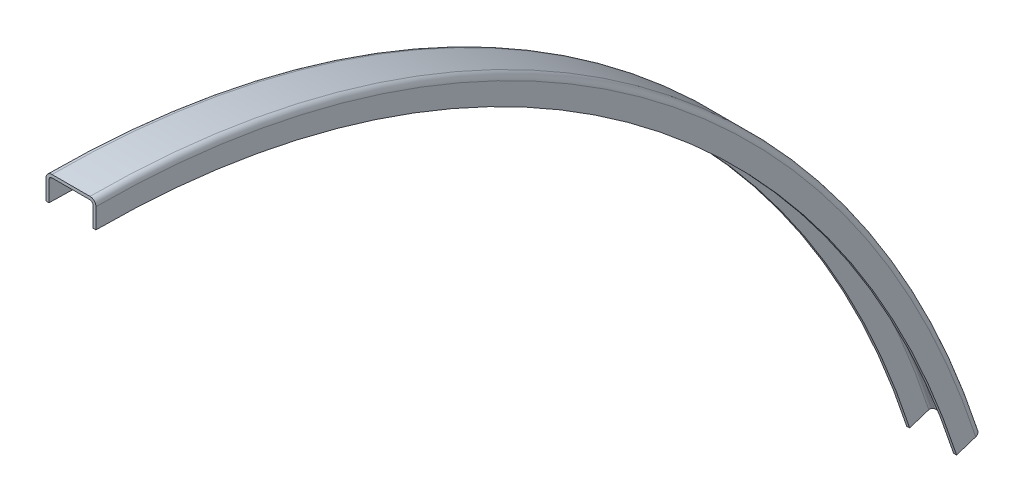
SolidWorks part; units mm, degrees
ref_plane "Front Plane" through (0, 0, 0) normal (0, 0, 1) x (1, 0, 0)
ref_plane "Top Plane" through (0, 0, 0) normal (0, 1, 0) x (1, 0, 0)
ref_plane "Right Plane" through (0, 0, 0) normal (1, 0, 0) x (0, 0, -1)
sketch "Sketch1" plane through (0, 0, 0) normal (0, 0, 1) x (1, 0, 0)
  line L0 (6.8425, 105.3307) -> (-44.1575, 105.3307)
  line L1 (-52.1575, 97.3307) -> (-52.1575, 70.3307)
  line L2 (-52.1575, 70.3307) -> (-48.1575, 70.3307)
  line L3 (-48.1575, 70.3307) -> (-48.1575, 97.3307)
  line L4 (-44.1575, 101.3307) -> (6.8425, 101.3307)
  line L5 (10.8425, 97.3307) -> (10.8425, 70.3307)
  line L6 (10.8425, 70.3307) -> (14.8425, 70.3307)
  line L7 (14.8425, 70.3307) -> (14.8425, 97.3307)
  line L8 (14.8425, -1144.6693) -> (-71.0301, -1144.6693)
  arc A0 (-48.1575, 97.3307) -> (-44.1575, 101.3307) centre (-44.1575, 97.3307) cw
  arc A1 (10.8425, 97.3307) -> (6.8425, 101.3307) centre (6.8425, 97.3307) ccw
  arc A2 (14.8425, 97.3307) -> (6.8425, 105.3307) centre (6.8425, 97.3307) ccw
  arc A3 (-52.1575, 97.3307) -> (-44.1575, 105.3307) centre (-44.1575, 97.3307) cw
  point P14 (14.8425, 105.3307)
  point P17 (-52.1575, 105.3307)
  dimension "D7" = 4
  dimension "D8" = 8
  dimension "D1" = 67
  dimension "D2" = 35
  dimension "D3" = 35
  dimension "D4" = 4
  dimension "D5" = 4
  dimension "D6" = 4
  dimension "D9" = 1250
revolve "Revolve1" add sketch "Sketch1" angle 72 about L8
